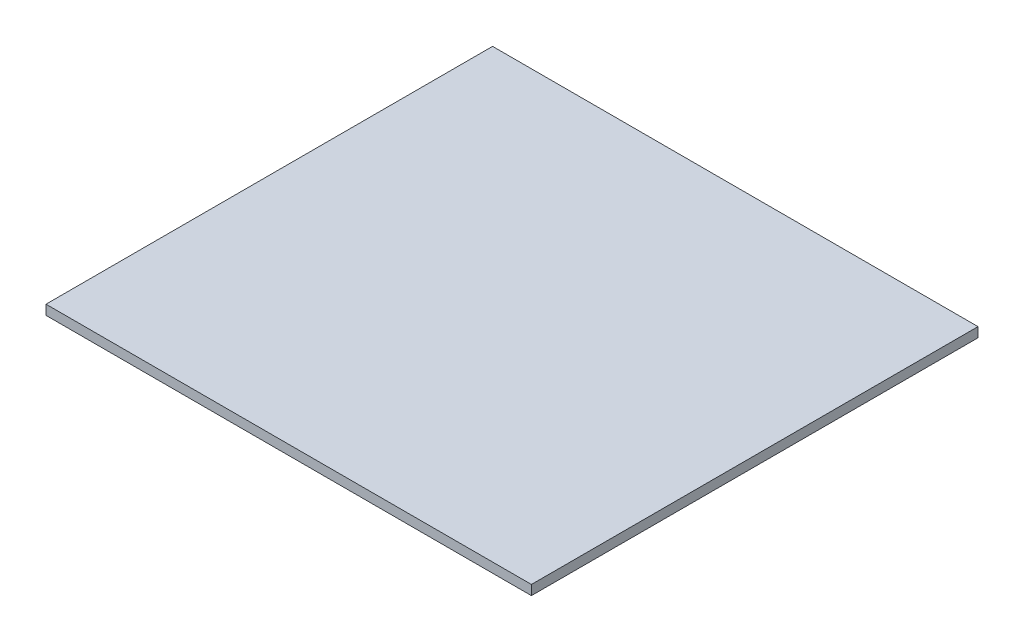
SolidWorks part; units mm, degrees
ref_plane "Front Plane" through (0, 0, 0) normal (0, 0, 1) x (1, 0, 0)
ref_plane "Top Plane" through (0, 0, 0) normal (0, 1, 0) x (1, 0, 0)
ref_plane "Right Plane" through (0, 0, 0) normal (1, 0, 0) x (0, 0, -1)
sketch "Sketch1" plane through (0, 0, 0) normal (0, 1, 0) x (1, 0, 0)
  line L1 (-125, -115) -> (125, -115)
  line L2 (-125, -115) -> (-125, 115)
  line L3 (-125, 115) -> (125, 115)
  line L4 (125, -115) -> (125, 115)
  line L5 (-125, -115) -> (125, 115) construction
  line L6 (-125, 115) -> (125, -115) construction
  point P0 (0, 0)
  dimension "D1" = 250
  dimension "D2" = 230
extrude "Boss-Extrude1" add sketch "Sketch1" along normal blind 5
